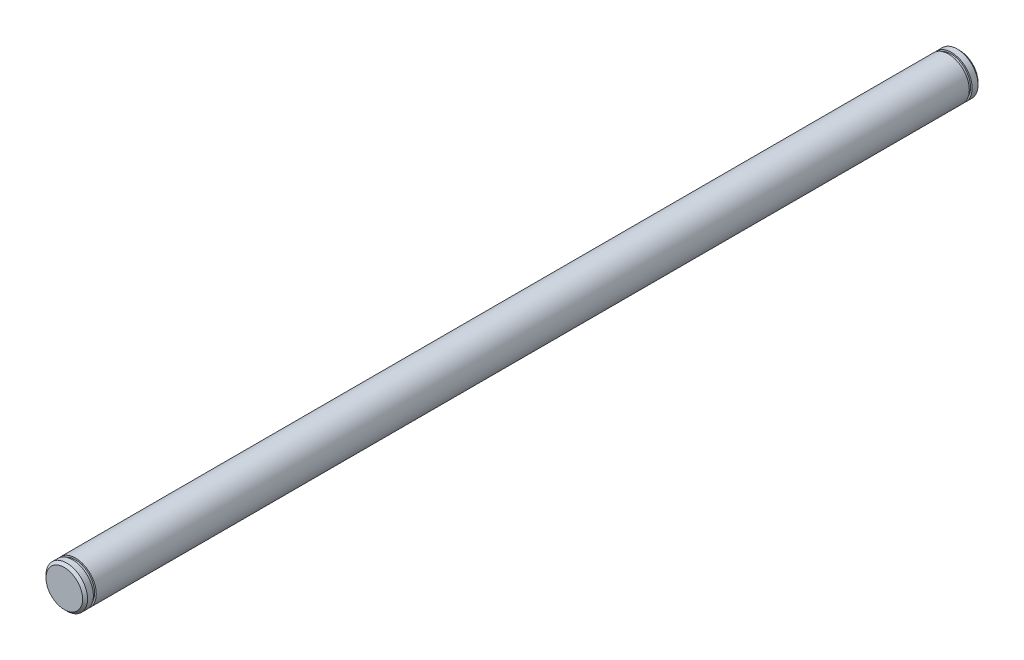
SolidWorks part; units mm, degrees
material "AISI 4130 Steel, annealed at 865C"
ref_plane "Front Plane" through (0, 0, 0) normal (0, 0, 1) x (1, 0, 0)
ref_plane "Top Plane" through (0, 0, 0) normal (0, 1, 0) x (1, 0, 0)
ref_plane "Right Plane" through (0, 0, 0) normal (1, 0, 0) x (0, 0, -1)
sketch "Sketch1" plane through (0, 0, 0) normal (0, 0, 1) x (1, 0, 0)
  circle A0 centre (0, 0) radius 6.35
  dimension "D1" = 12.7
extrude "Boss-Extrude1" add sketch "Sketch1" along normal mid plane 266.8016
sketch "Sketch2" plane through (0, 0, 133.4008) normal (0, 0, 1) x (1, 0, 0)
  circle A0 centre (0, 0) radius 5.8547
  dimension "D1" = 11.7094
extrude "Boss-Extrude2" add sketch "Sketch2" along normal blind 0.889
sketch "Sketch3" plane through (0, 0, 134.2898) normal (0, 0, 1) x (1, 0, 0)
  circle A0 centre (0, 0) radius 6.35
  dimension "D1" = 12.7
extrude "Boss-Extrude3" add sketch "Sketch3" along normal blind 2.54
chamfer "Chamfer1" distance 0.762 angle 45 1 edges at (6.35, 0, 136.8298)
mirror "Mirror1" about plane through (0, 0, 0) normal (0, 0, 1) of "Boss-Extrude3", "Boss-Extrude2", "Chamfer1"
